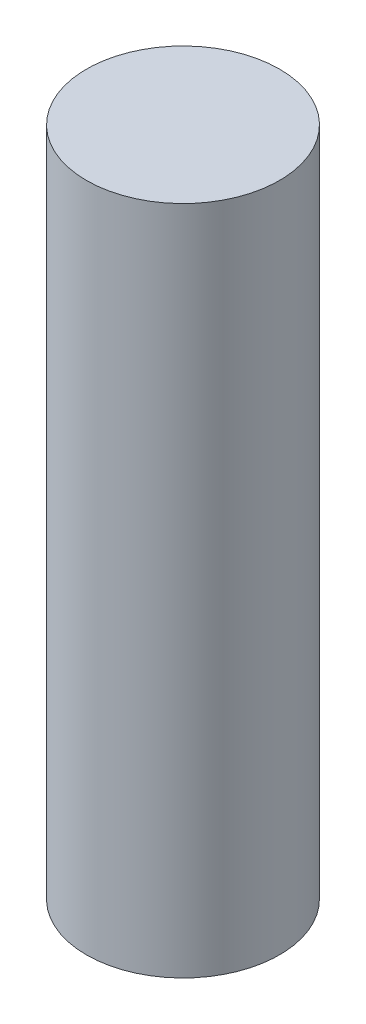
SolidWorks part; units mm, degrees
ref_plane "Front Plane" through (0, 0, 0) normal (0, 0, 1) x (1, 0, 0)
ref_plane "Top Plane" through (0, 0, 0) normal (0, 1, 0) x (1, 0, 0)
ref_plane "Right Plane" through (0, 0, 0) normal (1, 0, 0) x (0, 0, -1)
sketch "Sketch1" plane through (0, 0, 0) normal (0, 1, 0) x (1, 0, 0)
  circle A0 centre (0, 0) radius 2.95
  dimension "D1" = 5.9
extrude "Boss-Extrude1" add sketch "Sketch1" along normal blind 20.5
